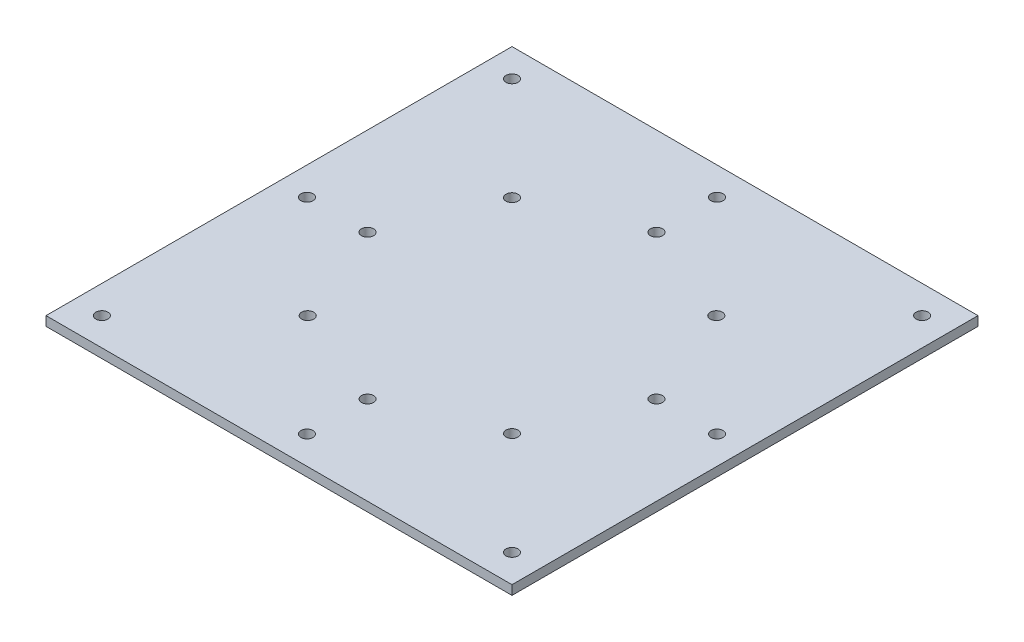
SolidWorks part; units mm, degrees
ref_plane "Front Plane" through (0, 0, 0) normal (0, 0, 1) x (1, 0, 0)
ref_plane "Top Plane" through (0, 0, 0) normal (0, 1, 0) x (1, 0, 0)
ref_plane "Right Plane" through (0, 0, 0) normal (1, 0, 0) x (0, 0, -1)
sketch "Sketch1" plane through (0, 0, 0) normal (0, 1, 0) x (1, 0, 0)
  line L1 (-125, -125) -> (125, -125)
  line L2 (-125, -125) -> (-125, 125)
  line L3 (-125, 125) -> (125, 125)
  line L4 (125, -125) -> (125, 125)
  line L5 (-125, -125) -> (125, 125) construction
  line L6 (-125, 125) -> (125, -125) construction
  circle A0 centre (-110, 110) radius 3.25
  circle A9 centre (0, 110) radius 3.25
  circle A10 centre (-54.8008, 54.8008) radius 3.25
  circle A11 centre (0, 77.5) radius 3.25
  circle A12 centre (54.8008, 54.8008) radius 3.25
  circle A13 centre (77.5, 0) radius 3.25
  circle A14 centre (54.8008, -54.8008) radius 3.25
  circle A15 centre (0, -77.5) radius 3.25
  circle A16 centre (-54.8008, -54.8008) radius 3.25
  circle A17 centre (-77.5, 0) radius 3.25
  circle A18 centre (110, 110) radius 3.25
  circle A20 centre (110, 0) radius 3.25
  circle A21 centre (0, -110) radius 3.25
  circle A22 centre (110, -110) radius 3.25
  circle A23 centre (-110, 0) radius 3.25
  circle A24 centre (-110, -110) radius 3.25
  circle A25 centre (0, 0) radius 3.25 [skipped]
  point P0 (0, 0)
  point P43 (0, 0)
  dimension "D3" = 6.5
  dimension "D7" = 6.5
  dimension "D1" = 250
  dimension "D2" = 250
  dimension "D4" = 15
  dimension "D8" = 77.5
  dimension "D5" = 3
  dimension "D6" = 3
  dimension "D9" = 8
extrude "Boss-Extrude1" add sketch "Sketch1" along normal blind 5
